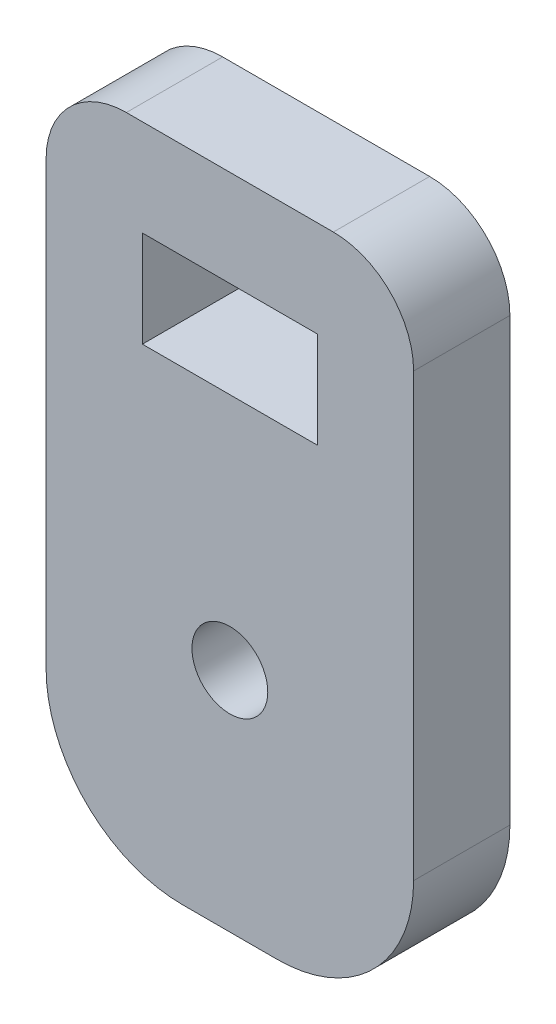
SolidWorks part; units mm, degrees
ref_plane "Front Plane" through (0, 0, 0) normal (0, 0, 1) x (1, 0, 0)
ref_plane "Top Plane" through (0, 0, 0) normal (0, 1, 0) x (1, 0, 0)
ref_plane "Right Plane" through (0, 0, 0) normal (1, 0, 0) x (0, 0, -1)
sketch "Sketch1" plane through (0, 0, 0) normal (0, 0, 1) x (1, 0, 0)
  line L0 (0, 58.42) -> (58.166, 58.42) construction
  line L1 (0, 0) -> (58.166, 0)
  line L2 (0, 0) -> (0, 104.14)
  line L3 (0, 104.14) -> (58.166, 104.14)
  line L4 (58.166, 0) -> (58.166, 104.14)
  dimension "D1" = 104.14
  dimension "D2" = 58.166
  dimension "D3" = 45.72
extrude "Boss-Extrude1" add sketch "Sketch1" along normal blind 15.24
sketch "Sketch2" plane through (0, 0, 15.24) normal (0, 0, 1) x (1, 0, 0)
  line L0 (0, 58.42) -> (58.166, 58.42) construction
  line L1 (0, 104.14) -> (0, 0) construction
  line L2 (58.166, 0) -> (58.166, 104.14) construction
  line L4 (15.24, 88.9) -> (42.926, 88.9)
  line L5 (15.24, 88.9) -> (15.24, 73.66)
  line L6 (15.24, 73.66) -> (42.926, 73.66)
  line L7 (42.926, 88.9) -> (42.926, 73.66)
  line L8 (0, 81.28) -> (15.24, 81.28) construction
  line L9 (42.926, 81.28) -> (58.166, 81.28) construction
  point P12 (0, 67.056)
  dimension "D1" = 45.72
  dimension "D2" = 15.24
  dimension "D4" = 15.24
  dimension "D3" = 15.24
  dimension "D5" = 27.686
extrude "Cut-Extrude1" cut sketch "Sketch2" against normal through all
sketch "Sketch7" plane through (0, 0, 15.24) normal (0, 0, 1) x (1, 0, 0)
  line L1 (0, 104.14) -> (0, 0) construction
  line L2 (58.166, 0) -> (58.166, 104.14) construction
  line L3 (58.166, 104.14) -> (0, 104.14) construction
  line L4 (0, 28.9) -> (58.166, 28.9) construction
  line L5 (0, 0) -> (58.166, 0) construction
  line L6 (29.083, 104.14) -> (29.083, 0) construction
  circle A0 centre (29.083, 35.9) radius 6
  circle A2 centre (29.083, 28.9) radius 15.5 construction
  circle A4 centre (13.583, 28.9) radius 2
  circle A5 centre (44.583, 28.9) radius 2
  circle A6 centre (37.2492, 15.7257) radius 2
  dimension "D1" = 12
  dimension "D3" = 31
  dimension "D2" = 4
  dimension "D4" = 28.9
  dimension "D5" = 7
extrude "Cut-Extrude2" cut sketch "Sketch7" against normal through all contours A0
fillet "Fillet1" radius 21.59 2 edges at (58.166, 0, 7.62) (0, 0, 7.62)
fillet "Fillet2" radius 12.7 2 edges at (58.166, 104.14, 7.62) (0, 104.14, 7.62)
equation "\"MDF\"= .3"
equation "\"Foamcore\"= .1"
equation "\"GMaterial\"= .6"
equation "\"CutDistance\" = .1"
equation "\"D1@Boss-Extrude1\"=\"GMaterial\""
equation "\"D1@Sketch1\"=3*\"GMaterial\" + 2.30"
equation "\"D1@Sketch2\"=3*\"GMaterial\""
equation "\"D2@Sketch2\"=\"GMaterial\""
equation "\"D4@Sketch2\"=\"GMaterial\""
equation "\"G\"=0.857891"
equation "\"D3@Sketch1\"=\"GMaterial\" * 3"
